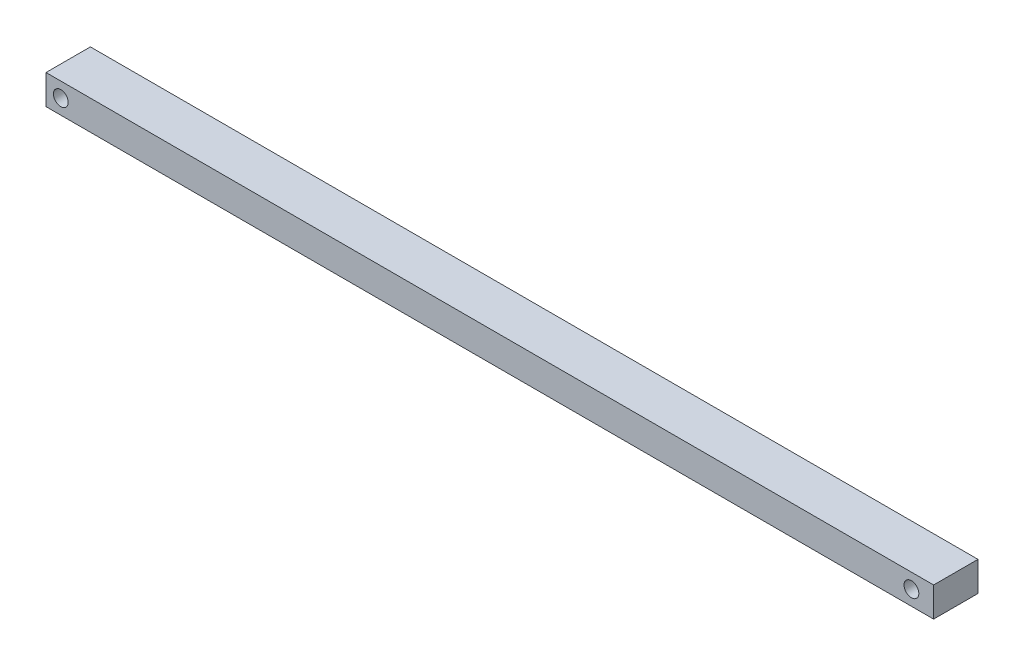
SolidWorks part; units mm, degrees
ref_plane "Front Plane" through (0, 0, 0) normal (0, 0, 1) x (1, 0, 0)
ref_plane "Top Plane" through (0, 0, 0) normal (0, 1, 0) x (1, 0, 0)
ref_plane "Right Plane" through (0, 0, 0) normal (1, 0, 0) x (0, 0, -1)
sketch "Sketch1" plane through (0, 0, 0) normal (0, 0, 1) x (1, 0, 0)
  line L0 (0, 10) -> (600, 10) construction
  line L1 (0, 0) -> (600, 0)
  line L2 (0, 0) -> (0, 20)
  line L3 (0, 20) -> (600, 20)
  line L4 (600, 0) -> (600, 20)
  circle A0 centre (10, 10) radius 5
  circle A1 centre (585, 10) radius 5
  dimension "D3" = 10
  dimension "D4" = 15
  dimension "D1" = 600
  dimension "D2" = 20
extrude "Boss-Extrude1" add sketch "Sketch1" against normal blind 30
